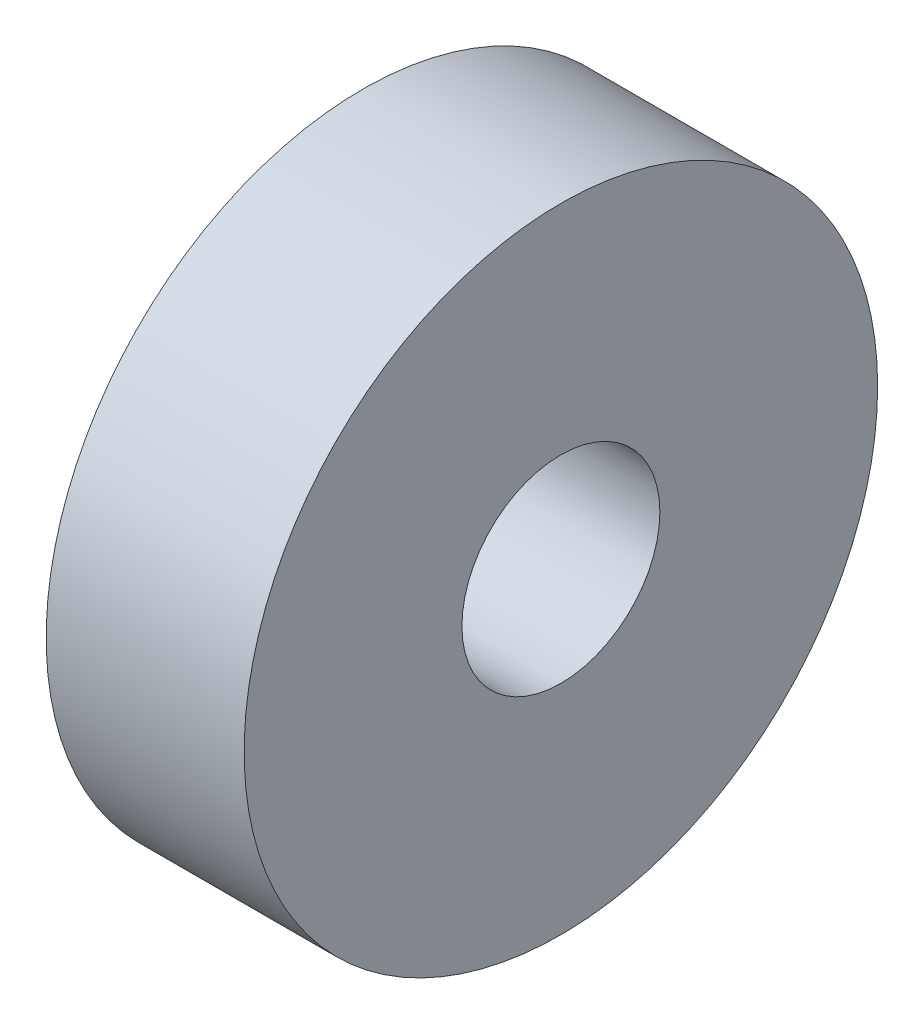
SolidWorks part; units mm, degrees
ref_plane "Front Plane" through (0, 0, 0) normal (0, 0, 1) x (1, 0, 0)
ref_plane "Top Plane" through (0, 0, 0) normal (0, 1, 0) x (1, 0, 0)
ref_plane "Right Plane" through (0, 0, 0) normal (1, 0, 0) x (0, 0, -1)
sketch "Sketch1" plane through (0, 0, 0) normal (1, 0, 0) x (0, 0, -1)
  circle A0 centre (0, 0) radius 2.5
  circle A1 centre (0, 0) radius 8
  dimension "D1" = 16
  dimension "D2" = 5
extrude "Boss-Extrude1" add sketch "Sketch1" along normal mid plane 5
